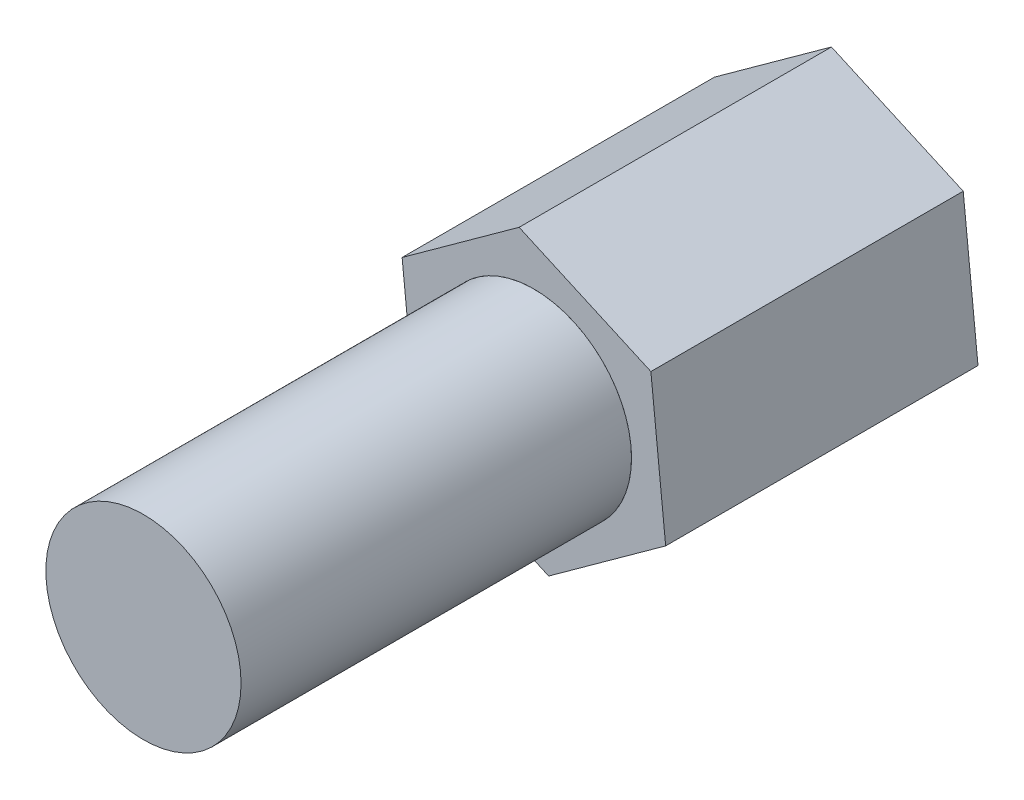
SolidWorks part; units mm, degrees
ref_plane "前视基准面" through (0, 0, 0) normal (0, 0, 1) x (1, 0, 0)
ref_plane "上视基准面" through (0, 0, 0) normal (0, 1, 0) x (1, 0, 0)
ref_plane "右视基准面" through (0, 0, 0) normal (1, 0, 0) x (0, 0, -1)
sketch "草图1" plane through (0, 0, 0) normal (0, 0, 1) x (1, 0, 0)
  line L2 (22.1216, 24.6787) -> (19.1249, 22.5117)
  line L3 (19.1249, 22.5117) -> (19.5033, 18.833)
  line L4 (19.5033, 18.833) -> (22.8784, 17.3213)
  line L5 (22.8784, 17.3213) -> (25.8751, 19.4883)
  line L6 (25.8751, 19.4883) -> (25.4967, 23.167)
  line L7 (25.4967, 23.167) -> (22.1216, 24.6787)
  circle A0 centre (22.5, 21) radius 3.2027 construction
extrude "凸台-拉伸1" add sketch "草图1" along normal up to surface (8 mm away)
sketch "草图3" plane through (0, 0, 8) normal (0, 0, 1) x (1, 0, 0)
  circle A0 centre (22.5, 21) radius 2.5 construction
  circle A1 centre (22.5, 21) radius 2.5
  dimension "D1" = 5
sketch "草图4" plane through (0, 0, 0) normal (0, 0, -1) x (-1, 0, 0)
  circle A0 centre (-22.5, 21) radius 2.5
  dimension "D1" = 5
extrude "切除-拉伸3" cut sketch "草图4" against normal blind 8 contours A0
sketch "草图5" plane through (0, 0, 8) normal (0, 0, 1) x (1, 0, 0)
  circle A0 centre (22.5, 21) radius 2.5
extrude "凸台-拉伸2" add sketch "草图5" along normal blind 10 separate body
